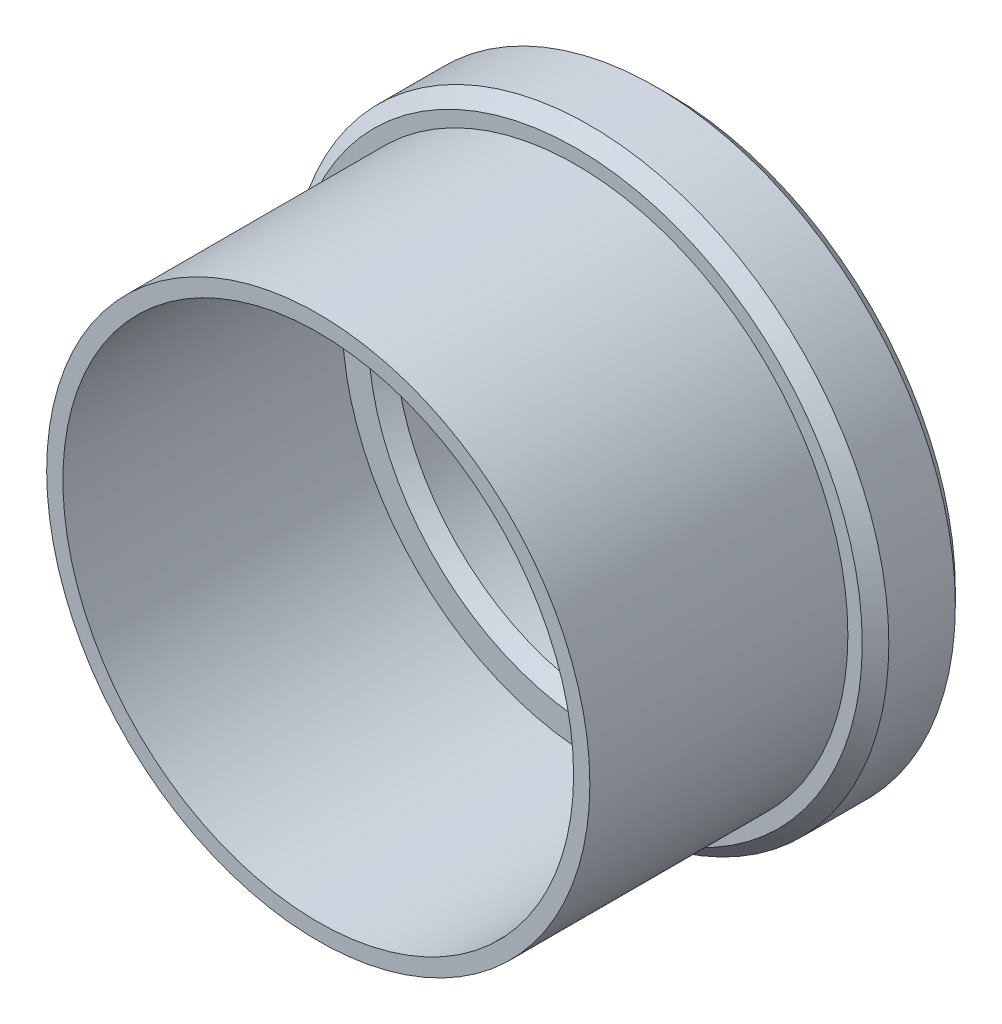
SolidWorks part; units mm, degrees
ref_plane "Alzado" through (0, 0, 0) normal (0, 0, 1) x (1, 0, 0)
ref_plane "Planta" through (0, 0, 0) normal (0, 1, 0) x (1, 0, 0)
ref_plane "Vista lateral" through (0, 0, 0) normal (1, 0, 0) x (0, 0, -1)
sketch "Croquis1" plane through (0, 0, 0) normal (1, 0, 0) x (0, 0, -1)
  line L0 (0, 0) -> (13.2, 0) construction
  line L1 (0, 9.6) -> (10.5, 9.6)
  line L2 (0, 10.21) -> (9.7, 10.21)
  line L3 (0, 10.21) -> (0, 9.6)
  line L4 (0, 9.6) -> (0, -0.0022) construction
  line L5 (10.2, 11.25) -> (12.7, 11.25)
  line L6 (11, 8.125) -> (13.2, 8.125)
  line L7 (13.2, 10.75) -> (13.2, 8.125)
  line L8 (13.2, 8.125) -> (13.2, 0) construction
  line L9 (9.7, 10.75) -> (9.7, 10.21)
  line L10 (10.5, 9.6) -> (10.5, 8.625)
  line L11 (12.7, 11.25) -> (13.2, 10.75)
  line L12 (9.7, 10.75) -> (10.2, 11.25)
  line L13 (10.5, 8.625) -> (11, 8.125)
  point P7 (9.7, 11.25)
  point P9 (13.2, 11.25)
  point P10 (10.5, 8.125)
  dimension "D1" = 13.2
  dimension "D2" = 19.2
  dimension "D3" = 20.42
  dimension "D4" = 22.5
  dimension "D5" = 16.25
  dimension "D6" = 3.5
  dimension "D7" = 10.5
revolve "Revolución1" add sketch "Croquis1" angle 360 about L0
